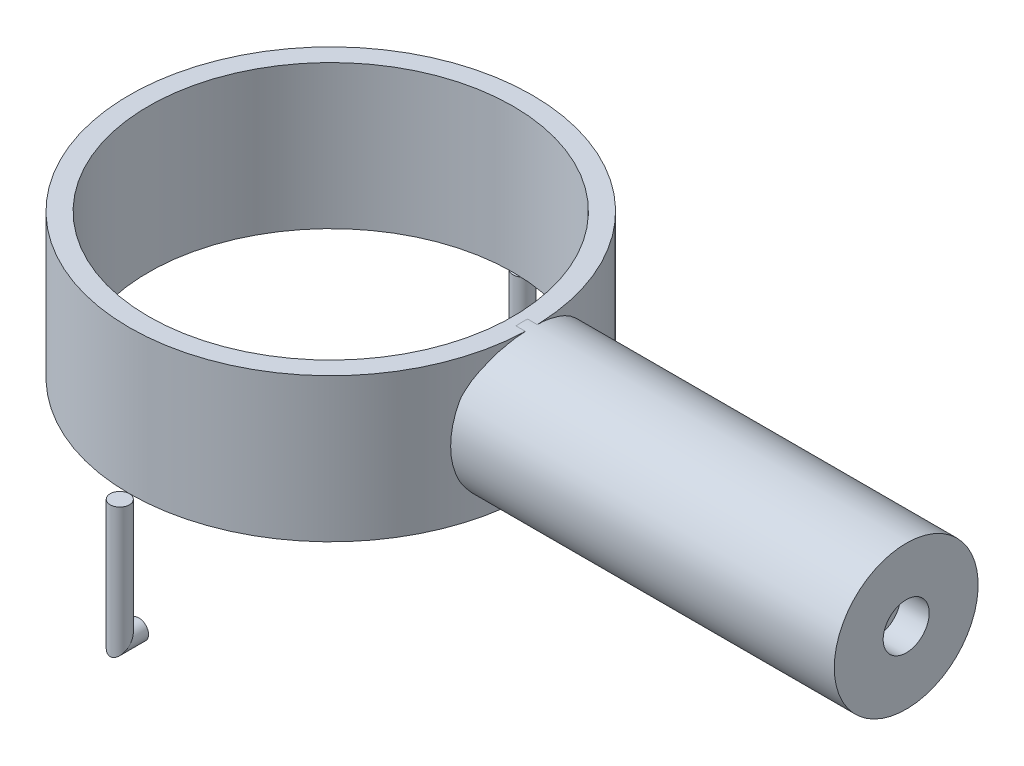
SolidWorks part; units mm, degrees
ref_plane "Front Plane" through (0, 0, 0) normal (0, 0, 1) x (1, 0, 0)
ref_plane "Top Plane" through (0, 0, 0) normal (0, 1, 0) x (1, 0, 0)
ref_plane "Right Plane" through (0, 0, 0) normal (1, 0, 0) x (0, 0, -1)
sketch "Sketch1" plane through (0, 0, 0) normal (0, 1, 0) x (1, 0, 0)
  circle A0 centre (0, 0) radius 19
  circle A1 centre (0, 0) radius 21
  dimension "D1" = 2
  dimension "D2" = 38
extrude "Boss-Extrude1" add sketch "Sketch1" along normal blind 15
ref_plane "Plane1" through (20, 0, 0) normal (1, 0, 0) x (0, 0, -1)
sketch "Sketch2" plane through (20, 0, 0) normal (1, 0, 0) x (0, 0, -1)
  circle A0 centre (0, 7.532) radius 7.5
extrude "Boss-Extrude2" add sketch "Sketch2" along normal blind 40 separate body
sketch "Sketch3" plane through (60, 0, 0) normal (1, 0, 0) x (0, 0, -1)
  circle A0 centre (0, 7.532) radius 2.4
extrude "Cut-Extrude1" cut sketch "Sketch3" against normal blind 3
sketch "Sketch5" plane through (0, 0, 0) normal (1, 0, 0) x (0, 0, -1)
  line L0 (-22, 0) -> (-22, -12.7165)
  line L1 (-22, -12.7165) -> (-20, -12.7165)
  dimension "D1" = 1
  dimension "D3" = 2
sweep "Sweep4" add path "Sketch5" circular profile diameter 2 parameters "D3"=2
sketch "Sketch89" plane through (0, 0, 0) normal (1, 0, 0) x (0, 0, -1)
  line L0 (20, -0.2349) -> (20, -12.9513)
  line L1 (20, -12.9513) -> (18, -12.9513)
  dimension "D1" = 2
  dimension "D2" = 1
sweep "Sweep5" add path "Sketch89" circular profile diameter 2 parameters "D3"=2
